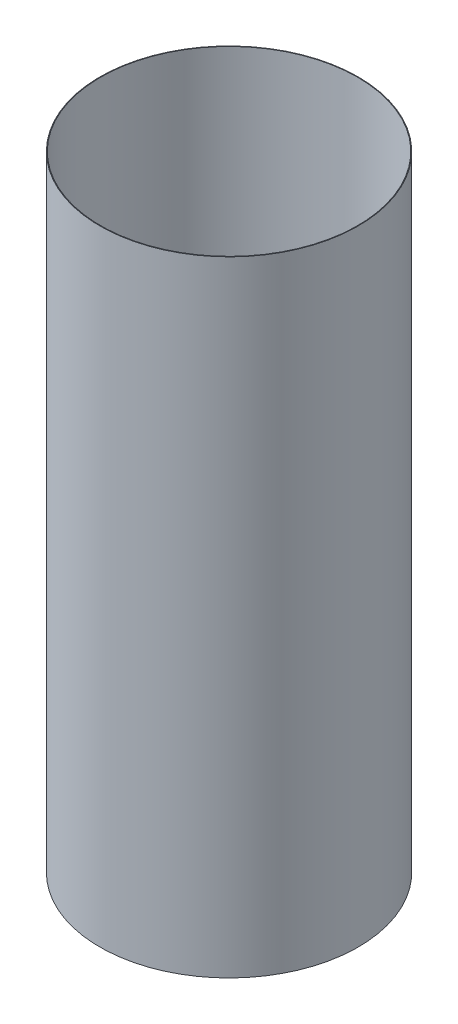
SolidWorks part; units mm, degrees
ref_plane "Front Plane" through (0, 0, 0) normal (0, 0, 1) x (1, 0, 0)
ref_plane "Top Plane" through (0, 0, 0) normal (0, 1, 0) x (1, 0, 0)
ref_plane "Right Plane" through (0, 0, 0) normal (1, 0, 0) x (0, 0, -1)
sketch "Sketch1" plane through (0, 0, 0) normal (0, 1, 0) x (1, 0, 0)
  circle A0 centre (0, 0) radius 36.449
  circle A1 centre (0, 0) radius 36.2712
  dimension "D2" = 72.898
  dimension "D1" = 0.1778
extrude "Boss-Extrude1" add sketch "Sketch1" along normal blind 176.2125
